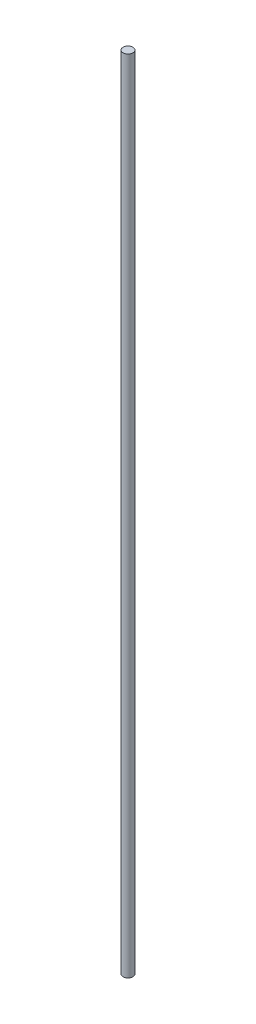
SolidWorks part; units mm, degrees
ref_plane "Front Plane" through (0, 0, 0) normal (0, 0, 1) x (1, 0, 0)
ref_plane "Top Plane" through (0, 0, 0) normal (0, 1, 0) x (1, 0, 0)
ref_plane "Right Plane" through (0, 0, 0) normal (1, 0, 0) x (0, 0, -1)
sketch "Sketch1" plane through (0, 0, 0) normal (0, 1, 0) x (1, 0, 0)
  circle A0 centre (0, 0) radius 11.25
  dimension "D1" = 22.5
extrude "Boss-Extrude1" add sketch "Sketch1" along normal blind 1828.8
